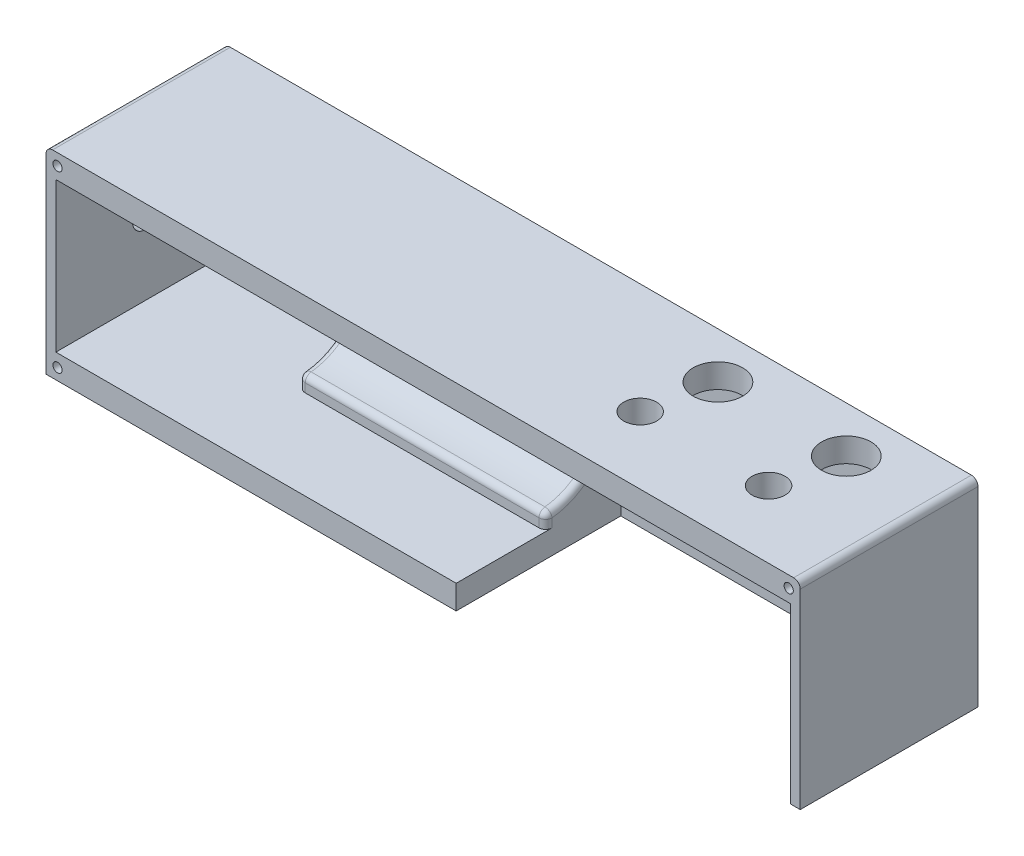
SolidWorks part; units mm, degrees
ref_plane "正面" through (0, 0, 0) normal (0, 0, 1) x (1, 0, 0)
ref_plane "平面" through (0, 0, 0) normal (0, 1, 0) x (1, 0, 0)
ref_plane "右側面" through (0, 0, 0) normal (1, 0, 0) x (0, 0, -1)
sketch "ｽｹｯﾁ1" plane through (0, 0, 0) normal (0, 0, 1) x (1, 0, 0)
  line L1 (0, 0) -> (255, 0) construction
  line L2 (0, 0) -> (0, 60) construction
  line L3 (0, 60) -> (255, 60) construction
  line L4 (255, 0) -> (255, 60) construction
  line L5 (3, 7.3) -> (49.6, 7.3)
  line L6 (3, 7.3) -> (3, 52.7)
  line L7 (3, 52.7) -> (49.6, 52.7)
  line L8 (49.6, 7.3) -> (49.6, 52.7)
  line L9 (49.6, 0) -> (3, 0)
  line L10 (49.6, 0) -> (49.6, 60)
  line L11 (49.6, 60) -> (3, 60)
  line L12 (3, 0) -> (3, 60)
  dimension "D1" = 255
  dimension "D2" = 60
  dimension "D3" = 45.4
  dimension "D4" = 46.6
  dimension "D5" = 3
  dimension "D6" = 7.3
extrude "ﾎﾞｽ - 押し出し1" add sketch "ｽｹｯﾁ1" along normal blind 54 contours L12 L9 L10 L5 | L12 L7 L10 L11
sketch "ｽｹｯﾁ2" plane through (0, 0, 0) normal (0, 0, -1) x (-1, 0, 0)
  line L1 (-49.6, 52.7) -> (-3, 52.7)
  line L2 (-49.6, 52.7) -> (-49.6, 7.3)
  line L3 (-49.6, 7.3) -> (-3, 7.3)
  line L4 (-3, 52.7) -> (-3, 7.3)
extrude "ﾎﾞｽ - 押し出し2" add sketch "ｽｹｯﾁ2" against normal blind 4
sketch "ｽｹｯﾁ3" plane through (3, 0, 0) normal (-1, 0, 0) x (0, 0, 1)
  line L0 (54, 0) -> (0, 0) construction
  line L1 (0, 60) -> (54, 60)
  line L2 (0, 60) -> (0, 0)
  line L3 (0, 0) -> (54, 0)
  line L4 (54, 60) -> (54, 0)
  dimension "D1" = 54
extrude "ﾎﾞｽ - 押し出し3" add sketch "ｽｹｯﾁ3" along normal blind 3
sketch "ｽｹｯﾁ4" plane through (3, 0, 0) normal (1, 0, 0) x (0, 0, -1)
  circle A0 centre (-26.8539, 29.8374) radius 3.8717
extrude "ｶｯﾄ - 押し出し1" cut sketch "ｽｹｯﾁ4" against normal blind 3
sketch "ｽｹｯﾁ5" plane through (49.6, 0, 0) normal (1, 0, 0) x (0, 0, -1)
  line L0 (-54, 0) -> (0, 0) construction
  line L1 (0, 60) -> (-26.8539, 60)
  line L2 (0, 60) -> (0, 0)
  line L3 (0, 0) -> (-26.8539, 0)
  line L4 (-26.8539, 60) -> (-26.8539, 0)
  circle A0 centre (-26.8539, 29.8374) radius 18
  line M1 (0, 0) -> (0, 60)
  line M2 (0, 60) -> (-54, 60)
  line M4 (-54, 52.7) -> (-4, 52.7)
  line M5 (-4, 52.7) -> (-4, 7.3)
  line M6 (-4, 7.3) -> (-54, 7.3)
  line M8 (-54, 0) -> (0, 0)
  dimension "D1" = 36
extrude "ﾎﾞｽ - 押し出し4" add sketch "ｽｹｯﾁ5" along normal blind 75 contours L4 M2 M4 M5 M6 M8 M1 | A0 L4 M6 M5 M4
sketch "ｽｹｯﾁ6" plane through (0, 0, 26.8539) normal (0, 0, 1) x (1, 0, 0)
  line L0 (124.6, 60) -> (124.6, 47.8374) construction
  line L1 (49.6, 60) -> (124.6, 60)
  line L2 (49.6, 60) -> (49.6, 52.7)
  line L3 (49.6, 52.7) -> (124.6, 52.7)
  line L4 (124.6, 60) -> (124.6, 52.7)
  line L5 (124.6, 11.8374) -> (124.6, 0) construction
  line L6 (49.6, 0) -> (124.6, 0)
  line L7 (49.6, 0) -> (49.6, 7.3)
  line L8 (49.6, 7.3) -> (124.6, 7.3)
  line L9 (124.6, 0) -> (124.6, 7.3)
  line L10 (3, 52.7) -> (49.6, 52.7) construction
  line L11 (49.6, 7.3) -> (3, 7.3) construction
extrude "ﾎﾞｽ - 押し出し5" add sketch "ｽｹｯﾁ6" along normal up to vertex (27.1461 mm away)
sketch "ｽｹｯﾁ7" plane through (124.6, 0, 0) normal (1, 0, 0) x (0, 0, -1)
  line L0 (0, 60) -> (-54, 60) construction
  line L1 (0, 0) -> (-4, 0)
  line L2 (0, 0) -> (0, 60)
  line L3 (0, 60) -> (-4, 60)
  line L4 (-4, 0) -> (-4, 60)
  dimension "D1" = 4
extrude "ﾎﾞｽ - 押し出し6" add sketch "ｽｹｯﾁ7" along normal blind 104.5
sketch "ｽｹｯﾁ8" plane through (0, 0, 4) normal (0, 0, 1) x (1, 0, 0)
  line L0 (124.6, 60) -> (124.6, 0) construction
  line L1 (144.6, 48) -> (183.6, 48)
  line L2 (144.6, 48) -> (144.6, 28)
  line L3 (144.6, 28) -> (183.6, 28)
  line L4 (183.6, 48) -> (183.6, 28)
  line L5 (183.6, 48) -> (222.6, 48)
  line L6 (183.6, 48) -> (183.6, 28)
  line L7 (183.6, 28) -> (222.6, 28)
  line L8 (222.6, 48) -> (222.6, 28)
  line L9 (229.1, 60) -> (124.6, 60) construction
  circle A0 centre (147.6, 31) radius 1.4
  circle A1 centre (180.6, 45) radius 1.4
  circle A2 centre (186.6, 31) radius 1.4
  circle A3 centre (219.6, 45) radius 1.4
  point P20 (0, 0)
  dimension "D8" = 14
  dimension "D10" = 2.8
  dimension "D11" = 2.8
  dimension "D16" = 2.8
  dimension "D17" = 2.8
  dimension "D1" = 39
  dimension "D2" = 20
  dimension "D3" = 39
  dimension "D4" = 20
  dimension "D5" = 20
  dimension "D6" = 12
  dimension "D7" = 12
  dimension "D9" = 33
  dimension "D12" = 3
  dimension "D13" = 3
  dimension "D14" = 33
  dimension "D15" = 14
  dimension "D18" = 3
  dimension "D19" = 3
extrude "ｶｯﾄ - 押し出し2" cut sketch "ｽｹｯﾁ8" against normal blind 75 contours A0 | A1 | A2 | A3
sketch "ｽｹｯﾁ10" plane through (0, 60, 0) normal (0, 1, 0) x (1, 0, 0)
  line L0 (229.1, 0) -> (229.1, -4) construction
  line L1 (124.6, -4) -> (229.1, -4)
  line L2 (124.6, -4) -> (124.6, -54)
  line L3 (124.6, -54) -> (229.1, -54)
  line L4 (229.1, -4) -> (229.1, -54)
  line L5 (124.6, -54) -> (0, -54) construction
extrude "ﾎﾞｽ - 押し出し7" add sketch "ｽｹｯﾁ10" against normal up to vertex
sketch "ｽｹｯﾁ11" plane through (0, 52.7, 0) normal (0, -1, 0) x (-1, 0, 0)
  line L0 (-229.1, -4) -> (-124.6, -4) construction
  line L2 (-124.6, -4) -> (-124.6, -26.8539) construction
  circle A0 centre (-164.1, -14) radius 7.5
  circle A1 centre (-203.1, -14) radius 7.5
  circle A2 centre (-199.0752, -33.5908) radius 5
  circle A3 centre (-160.0752, -33.5908) radius 5
  dimension "D1" = 15
  dimension "D2" = 15
  dimension "D7" = 10
  dimension "D8" = 10
  dimension "D3" = 10
  dimension "D4" = 10
  dimension "D5" = 39.5
  dimension "D6" = 39
  dimension "D9" = 20
  dimension "D10" = 20
extrude "ｶｯﾄ - 押し出し3" cut sketch "ｽｹｯﾁ11" against normal blind 16
sketch "ｽｹｯﾁ12" plane through (229.1, 0, 0) normal (1, 0, 0) x (0, 0, -1)
  line L1 (0, 60) -> (-54, 60)
  line L2 (0, 60) -> (0, 0)
  line L3 (0, 0) -> (-54, 0)
  line L4 (-54, 60) -> (-54, 0)
extrude "ﾎﾞｽ - 押し出し8" add sketch "ｽｹｯﾁ12" against normal blind 3
sketch "ｽｹｯﾁ13" plane through (0, 0, 54) normal (0, 0, 1) x (1, 0, 0)
  line L0 (124.6, 0) -> (0, 0) construction
  line L1 (0, 0) -> (0, 60) construction
  line L3 (229.1, 60) -> (0, 60) construction
  line L4 (229.1, 0) -> (229.1, 60) construction
  circle A0 centre (3.5, 3.5) radius 1.4
  circle A1 centre (3.5, 56.5) radius 1.4
  circle A2 centre (225.6, 56.5) radius 1.4
  point P12 (0, 0)
  dimension "D1" = 2.8
  dimension "D2" = 2.8
  dimension "D3" = 2.8
  dimension "D4" = 3.5
  dimension "D5" = 3.5
  dimension "D6" = 3.5
  dimension "D7" = 3.5
  dimension "D8" = 3.5
  dimension "D9" = 3.5
extrude "ｶｯﾄ - 押し出し4" cut sketch "ｽｹｯﾁ13" against normal blind 15
fillet "ﾌｨﾚｯﾄ1" radius 2 8 edges at (49.6, 9.5687, 26.8539) (124.6, 9.5687, 26.8539) (87.1, 11.8374, 26.8539) (87.1, 47.8374, 26.8539) (124.6, 29.8374, 8.8539) (124.6, 50.2687, 26.8539) (49.6, 29.8374, 8.8539) (49.6, 50.2687, 26.8539)
fillet "ﾌｨﾚｯﾄ2" radius 2 2 edges at (0, 60, 27) (229.1, 60, 27)
